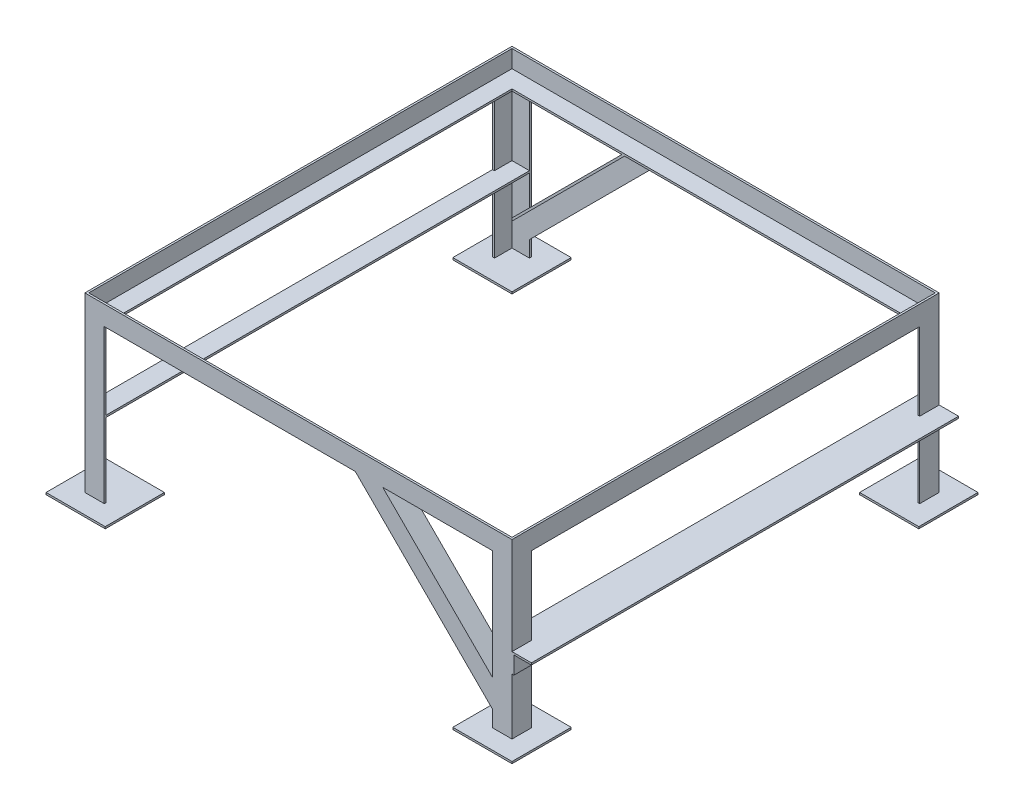
SolidWorks part; units mm, degrees
ref_plane "Спереди" through (0, 0, 0) normal (0, 0, 1) x (1, 0, 0)
ref_plane "Сверху" through (0, 0, 0) normal (0, 1, 0) x (1, 0, 0)
ref_plane "Справа" through (0, 0, 0) normal (1, 0, 0) x (0, 0, -1)
sketch "Эскиз1" plane through (0, 0, 0) normal (0, 1, 0) x (1, 0, 0)
  line L0 (-500, -500) -> (-500, 500)
  line L1 (-550, -550) -> (550, -550)
  line L2 (-550, -550) -> (-550, 550)
  line L3 (-550, 550) -> (550, 550)
  line L4 (550, -550) -> (550, 550)
  line L5 (-550, -550) -> (550, 550) construction
  line L6 (-550, 550) -> (550, -550) construction
  line L7 (-500, 500) -> (500, 500)
  line L8 (500, -500) -> (500, 500)
  line L9 (-500, -500) -> (500, -500)
  point P0 (0, 0)
  dimension "D1" = 1100
  dimension "D2" = 1100
  dimension "D3" = 50
extrude "Бобышка-Вытянуть1" add sketch "Эскиз1" along normal blind 5
sketch "Эскиз2" plane through (0, 5, 0) normal (0, -1, 0) x (1, 0, 0)
  line L0 (-545, 545) -> (545, 545)
  line L1 (-550, 550) -> (550, 550)
  line L2 (-550, 550) -> (-550, -550)
  line L3 (-550, -550) -> (550, -550)
  line L4 (550, 550) -> (550, -550)
  line L5 (545, 545) -> (545, -545)
  line L6 (-545, -545) -> (545, -545)
  line L7 (-545, 545) -> (-545, -545)
  dimension "D1" = 5
extrude "Бобышка-Вытянуть2" add sketch "Эскиз2" against normal blind 45
sketch "Эскиз3" plane through (0, 0, 0) normal (0, -1, 0) x (1, 0, 0)
  line L0 (0, 0) -> (50.6984, 0) construction
  line L1 (550, 550) -> (500, 550)
  line L2 (550, 550) -> (550, 500)
  line L3 (550, 500) -> (545, 500)
  line L4 (500, 550) -> (500, 545)
  line L5 (545, -500) -> (545, -545)
  line L6 (500, -545) -> (545, -545)
  line L7 (500, 545) -> (545, 545)
  line L8 (545, 500) -> (545, 545)
  line L9 (500, -550) -> (500, -545)
  line L10 (550, -500) -> (545, -500)
  line L11 (550, -550) -> (550, -500)
  line L12 (550, -550) -> (500, -550)
  line L13 (0, 0) -> (0, 65.4762) construction
  line L14 (-550, -550) -> (-500, -550)
  line L15 (-550, -550) -> (-550, -500)
  line L16 (-550, -500) -> (-545, -500)
  line L17 (-500, -550) -> (-500, -545)
  line L18 (-545, 500) -> (-545, 545)
  line L19 (-500, 545) -> (-545, 545)
  line L20 (-500, -545) -> (-545, -545)
  line L21 (-545, -500) -> (-545, -545)
  line L22 (-500, 550) -> (-500, 545)
  line L23 (-550, 500) -> (-545, 500)
  line L24 (-550, 550) -> (-550, 500)
  line L25 (-550, 550) -> (-500, 550)
  dimension "D1" = 50
  dimension "D2" = 5
extrude "Бобышка-Вытянуть3" add sketch "Эскиз3" along normal blind 400
sketch "Эскиз4" plane through (0, -400, 0) normal (0, -1, 0) x (1, 0, 0)
  line L0 (500, 547.5) -> (547.5, 500) construction
  line L1 (500, 550) -> (500, 545) construction
  line L2 (545, 500) -> (550, 500) construction
  line L3 (0, 0) -> (71.8664, 0) construction
  line L4 (447.5, 447.5) -> (600, 447.5)
  line L5 (447.5, 447.5) -> (447.5, 600)
  line L6 (447.5, 600) -> (600, 600)
  line L7 (600, 447.5) -> (600, 600)
  line L8 (447.5, 447.5) -> (600, 600) construction
  line L9 (447.5, 600) -> (600, 447.5) construction
  line L10 (447.5, -600) -> (600, -447.5) construction
  line L11 (447.5, -447.5) -> (600, -600) construction
  line L12 (500, -547.5) -> (547.5, -500) construction
  line L13 (600, -447.5) -> (600, -600)
  line L14 (447.5, -600) -> (600, -600)
  line L15 (447.5, -447.5) -> (447.5, -600)
  line L16 (447.5, -447.5) -> (600, -447.5)
  line L17 (0, 0) -> (0, 118.4902) construction
  line L18 (-500, -547.5) -> (-547.5, -500) construction
  line L19 (-447.5, -447.5) -> (-600, -600) construction
  line L20 (-447.5, -600) -> (-600, -447.5) construction
  line L21 (-447.5, 600) -> (-600, 447.5) construction
  line L22 (-447.5, 447.5) -> (-600, 600) construction
  line L23 (-500, 547.5) -> (-547.5, 500) construction
  line L24 (-447.5, -447.5) -> (-600, -447.5)
  line L25 (-447.5, -447.5) -> (-447.5, -600)
  line L26 (-447.5, -600) -> (-600, -600)
  line L27 (-600, -447.5) -> (-600, -600)
  line L28 (-600, 447.5) -> (-600, 600)
  line L29 (-447.5, 600) -> (-600, 600)
  line L30 (-447.5, 447.5) -> (-447.5, 600)
  line L31 (-447.5, 447.5) -> (-600, 447.5)
  point P6 (523.75, 523.75)
  point P20 (523.75, -523.75)
  point P34 (-523.75, -523.75)
  point P35 (-523.75, 523.75)
  dimension "D1" = 152.5
  dimension "D2" = 152.5
extrude "Бобышка-Вытянуть4" add sketch "Эскиз4" against normal blind 5
sketch "Эскиз6" plane through (0, 0, -545) normal (0, 0, 1) x (1, 0, 0)
  line L0 (500, -395) -> (500, 0) construction
  line L1 (500, -200) -> (550, -200)
  line L2 (500, -200) -> (500, -205)
  line L3 (545, -250) -> (550, -250)
  line L4 (550, -200) -> (550, -250)
  line L5 (550, 50) -> (550, -395) construction
  line L6 (600, -400) -> (447.5, -400) construction
  line L7 (0, 0) -> (0, -227.3998) construction
  line L8 (-545, -250) -> (-545, -205)
  line L9 (500, -205) -> (545, -205)
  line L10 (545, -250) -> (545, -205)
  line L11 (-500, -205) -> (-545, -205)
  line L12 (-550, -200) -> (-550, -250)
  line L13 (-545, -250) -> (-550, -250)
  line L14 (-500, -200) -> (-500, -205)
  line L15 (-500, -200) -> (-550, -200)
  dimension "D1" = 5
  dimension "D2" = 200
extrude "Бобышка-Вытянуть6" add sketch "Эскиз6" along normal up to surface (1090 mm away) up to face at (522.5, -197.5, 545)
sketch "Эскиз7" plane through (0, 0, 550) normal (0, 0, 1) x (1, 0, 0)
  line L0 (146.4466, 0) -> (217.1573, 0)
  line L1 (-500, 0) -> (500, 0) construction
  line L2 (217.1573, 0) -> (500, -282.8427)
  line L3 (500, -395) -> (500, 0) construction
  line L4 (500, -282.8427) -> (500, -353.5534)
  line L5 (500, -353.5534) -> (146.4466, 0)
  dimension "D1" = 50
  dimension "D2" = 45
  dimension "D3" = 500
extrude "Бобышка-Вытянуть7" add sketch "Эскиз7" against normal blind 5
sketch "Эскиз8" plane through (0, 0, 545) normal (0, 0, -1) x (-1, 0, 0)
  line L0 (-217.1573, 0) -> (-210.0862, 0)
  line L1 (-500, 0) -> (500, 0) construction
  line L2 (-217.1573, 0) -> (-146.4466, 0) construction
  line L3 (-210.0862, 0) -> (-500, -289.9138)
  line L4 (-500, -395) -> (-500, 0) construction
  line L5 (-500, -289.9138) -> (-500, -282.8427)
  line L6 (-500, -282.8427) -> (-217.1573, 0) construction
  line L7 (-500, -282.8427) -> (-217.1573, 0)
  dimension "D1" = 5
extrude "Бобышка-Вытянуть8" add sketch "Эскиз8" along normal blind 45
sketch "Эскиз9" plane through (0, 0, -550) normal (0, 0, -1) x (-1, 0, 0)
  line L0 (146.4466, 0) -> (500, -353.5534)
  line L1 (-500, 0) -> (500, 0) construction
  line L2 (500, -395) -> (500, 0) construction
  line L3 (500, -353.5534) -> (500, -282.8427)
  line L4 (500, -282.8427) -> (217.1573, 0)
  line L5 (217.1573, 0) -> (146.4466, 0)
  dimension "D1" = 50
  dimension "D2" = 45
  dimension "D3" = 500
extrude "Бобышка-Вытянуть9" add sketch "Эскиз9" against normal blind 5
sketch "Эскиз10" plane through (0, 0, -545) normal (0, 0, 1) x (1, 0, 0)
  line L0 (-217.1573, 0) -> (-210.0862, 0)
  line L1 (-500, 0) -> (146.4466, 0) construction
  line L2 (-210.0862, 0) -> (-500, -289.9138)
  line L3 (-500, -395) -> (-500, 0) construction
  line L4 (-500, -289.9138) -> (-500, -282.8427)
  line L5 (-500, -282.8427) -> (-217.1573, 0)
  dimension "D1" = 5
extrude "Бобышка-Вытянуть10" add sketch "Эскиз10" along normal blind 45
sketch "Эскиз11" plane through (0, 0, 550) normal (0, 0, 1) x (1, 0, 0)
  line L0 (550, 50) -> (550, -395) construction
  line L1 (550, -250) -> (555, -250)
  line L2 (550, -250) -> (550, -200)
  line L3 (550, -200) -> (600, -200)
  line L4 (600, -205) -> (600, -200)
  line L8 (600, -205) -> (555, -205)
  line L9 (555, -250) -> (555, -205)
  dimension "D1" = 5
  dimension "D2" = 50
extrude "Бобышка-Вытянуть11" add sketch "Эскиз11" against normal up to surface (1100 mm away) up to face at (-16.2718, -203.7282, -550)
